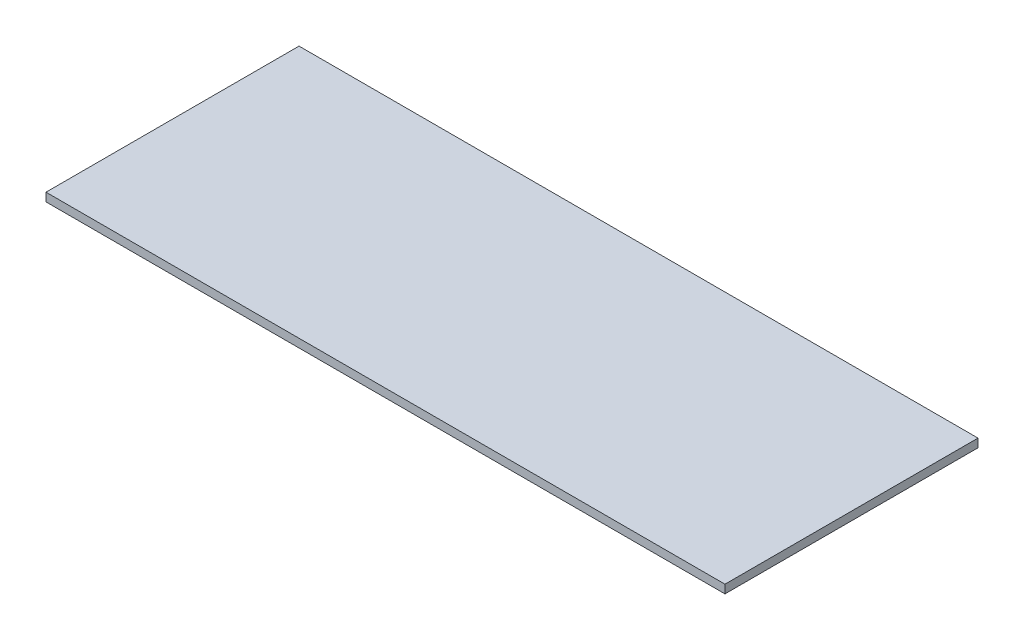
SolidWorks part; units mm, degrees
ref_plane "Front Plane" through (0, 0, 0) normal (0, 0, 1) x (1, 0, 0)
ref_plane "Top Plane" through (0, 0, 0) normal (0, 1, 0) x (1, 0, 0)
ref_plane "Right Plane" through (0, 0, 0) normal (1, 0, 0) x (0, 0, -1)
sketch "Sketch1" plane through (0, 0, 0) normal (0, 1, 0) x (1, 0, 0)
  line L0 (0, 88.9) -> (0, -88.9) construction
  line L1 (-381, 88.9) -> (381, 88.9)
  line L2 (-381, 88.9) -> (-381, -88.9)
  line L3 (-381, -88.9) -> (381, -88.9)
  line L4 (381, 88.9) -> (381, -88.9)
  line L5 (-381, 39.4607) -> (-381, 65.7679)
  line L7 (-381, 65.7679) -> (-381, 88.9)
  line L14 (-325.0712, -88.9) -> (-381, -88.9)
  line L19 (381, 65.7679) -> (381, 88.9)
  line L22 (-325.0712, 88.9) -> (-381, 88.9)
  line L29 (381, 39.4607) -> (381, 65.7679)
  line L33 (-381, 13.1536) -> (-381, 39.4607)
  line L37 (381, 13.1536) -> (381, 39.4607)
  line L41 (-381, -13.1536) -> (-381, 13.1536)
  line L45 (381, -13.1536) -> (381, 13.1536)
  line L49 (-381, -39.4607) -> (-381, -13.1536)
  line L53 (381, -39.4607) -> (381, -13.1536)
  line L57 (-381, -65.7679) -> (-381, -39.4607)
  line L61 (381, -65.7679) -> (381, -39.4607)
  line L65 (-381, -88.9) -> (-381, -65.7679)
  line L69 (381, -88.9) -> (381, -65.7679)
  line L74 (-265.9673, -88.9) -> (-325.0712, -88.9)
  line L78 (-265.9673, 88.9) -> (-325.0712, 88.9)
  line L82 (-206.8635, -88.9) -> (-265.9673, -88.9)
  line L86 (-206.8635, 88.9) -> (-265.9673, 88.9)
  line L90 (-147.7596, -88.9) -> (-206.8635, -88.9)
  line L93 (-147.7596, 88.9) -> (-147.7596, 92.075)
  line L94 (-147.7596, 88.9) -> (-206.8635, 88.9)
  line L98 (-88.6558, -88.9) -> (-147.7596, -88.9)
  line L102 (-88.6558, 88.9) -> (-147.7596, 88.9)
  line L103 (-147.7596, 88.9) -> (-147.7596, 92.075)
  line L105 (-29.5519, -88.9) -> (-29.5519, -92.075)
  line L106 (-29.5519, -88.9) -> (-88.6558, -88.9)
  line L110 (-29.5519, 88.9) -> (-88.6558, 88.9)
  line L114 (29.5519, -88.9) -> (-29.5519, -88.9)
  line L115 (-29.5519, -88.9) -> (-29.5519, -92.075)
  line L118 (29.5519, 88.9) -> (-29.5519, 88.9)
  line L122 (88.6558, -88.9) -> (29.5519, -88.9)
  line L126 (88.6558, 88.9) -> (29.5519, 88.9)
  line L130 (147.7596, -88.9) -> (88.6558, -88.9)
  line L134 (147.7596, 88.9) -> (88.6558, 88.9)
  line L138 (206.8635, -88.9) -> (147.7596, -88.9)
  line L142 (206.8635, 88.9) -> (147.7596, 88.9)
  line L146 (265.9673, -88.9) -> (206.8635, -88.9)
  line L150 (265.9673, 88.9) -> (206.8635, 88.9)
  line L186 (325.0712, -88.9) -> (265.9673, -88.9)
  line L190 (325.0712, 88.9) -> (265.9673, 88.9)
  line L194 (381, -88.9) -> (325.0712, -88.9)
  line L198 (381, 88.9) -> (325.0712, 88.9)
  point P8 (0, 88.9)
  point P9 (0, 0)
  dimension "D1" = 762
  dimension "D2" = 177.8
  dimension "D4" = 7
  dimension "D7" = 13
extrude "Boss-Extrude1" add sketch "Sketch1" along normal blind 6.35
sketch "Sketch4" [suppressed] plane through (0, 0, 0) normal (0, 1, 0) x (1, 0, 0)
  line L0 (0.0158, 88.9) -> (0.0158, -88.9) construction
  line L1 (-380.9842, 88.9) -> (381.0158, 88.9)
  line L2 (-380.9842, 88.9) -> (-380.9842, -88.9)
  line L3 (-380.9842, -88.9) -> (381.0158, -88.9)
  line L4 (381.0158, 88.9) -> (381.0158, -88.9)
  line L5 (-381, 39.4607) -> (-381, 65.7679)
  line L6 (-380.9842, 65.7679) -> (-384.1592, 65.7679)
  line L7 (-380.9842, 65.7679) -> (-380.9842, 92.075)
  line L8 (-380.9842, 92.075) -> (-384.1592, 92.075)
  line L9 (-384.1592, 65.7679) -> (-384.1592, 92.075)
  line L10 (-325.0554, -88.9) -> (-384.1592, -88.9)
  line L11 (-325.0554, -88.9) -> (-325.0554, -92.075)
  line L12 (-325.0554, -92.075) -> (-384.1592, -92.075)
  line L13 (-384.1592, -88.9) -> (-384.1592, -92.075)
  line L14 (381.0158, 65.7679) -> (384.1908, 65.7679)
  line L15 (381.0158, 65.7679) -> (381.0158, 92.075)
  line L16 (381.0158, 92.075) -> (384.1908, 92.075)
  line L17 (384.1908, 65.7679) -> (384.1908, 92.075)
  line L18 (-325.0554, 88.9) -> (-384.1592, 88.9)
  line L19 (-325.0554, 88.9) -> (-325.0554, 92.075)
  line L20 (-325.0554, 92.075) -> (-384.1592, 92.075)
  line L21 (-384.1592, 88.9) -> (-384.1592, 92.075)
  line L22 (-381, 39.4607) -> (-384.175, 39.4607)
  line L23 (-384.175, 39.4607) -> (-384.1592, 65.7679)
  line L24 (-381, 65.7679) -> (-384.1592, 65.7679)
  line L25 (381, 39.4607) -> (381, 65.7679)
  line L26 (381, 39.4607) -> (384.175, 39.4607)
  line L27 (384.175, 39.4607) -> (384.175, 65.7679)
  line L28 (381, 65.7679) -> (384.175, 65.7679)
  line L29 (-381, 13.1536) -> (-381, 39.4607)
  line L30 (-381, 13.1536) -> (-384.175, 13.1536)
  line L31 (-384.175, 13.1536) -> (-384.175, 39.4607)
  line L32 (-381, 39.4607) -> (-384.175, 39.4607)
  line L33 (381, 13.1536) -> (381, 39.4607)
  line L34 (381, 13.1536) -> (384.175, 13.1536)
  line L35 (384.175, 13.1536) -> (384.175, 39.4607)
  line L36 (381, 39.4607) -> (384.175, 39.4607)
  line L37 (-381, -13.1536) -> (-381, 13.1536)
  line L38 (-381, -13.1536) -> (-384.175, -13.1536)
  line L39 (-384.175, -13.1536) -> (-384.175, 13.1536)
  line L40 (-381, 13.1536) -> (-384.175, 13.1536)
  line L41 (381, -13.1536) -> (381, 13.1536)
  line L42 (381, -13.1536) -> (384.175, -13.1536)
  line L43 (384.175, -13.1536) -> (384.175, 13.1536)
  line L44 (381, 13.1536) -> (384.175, 13.1536)
  line L45 (-381, -39.4607) -> (-381, -13.1536)
  line L46 (-381, -39.4607) -> (-384.175, -39.4607)
  line L47 (-384.175, -39.4607) -> (-384.175, -13.1536)
  line L48 (-381, -13.1536) -> (-384.175, -13.1536)
  line L49 (381, -39.4607) -> (381, -13.1536)
  line L50 (381, -39.4607) -> (384.175, -39.4607)
  line L51 (384.175, -39.4607) -> (384.175, -13.1536)
  line L52 (381, -13.1536) -> (384.175, -13.1536)
  line L53 (-381, -65.7679) -> (-381, -39.4607)
  line L54 (-381, -65.7679) -> (-384.175, -65.7679)
  line L55 (-384.175, -65.7679) -> (-384.175, -39.4607)
  line L56 (-381, -39.4607) -> (-384.175, -39.4607)
  line L57 (381, -65.7679) -> (381, -39.4607)
  line L58 (381, -65.7679) -> (384.175, -65.7679)
  line L59 (384.175, -65.7679) -> (384.175, -39.4607)
  line L60 (381, -39.4607) -> (384.175, -39.4607)
  line L61 (-381, -92.075) -> (-381, -65.7679)
  line L62 (-381, -92.075) -> (-384.175, -92.075)
  line L63 (-384.175, -92.075) -> (-384.175, -65.7679)
  line L64 (-381, -65.7679) -> (-384.175, -65.7679)
  line L65 (381, -92.075) -> (381, -65.7679)
  line L66 (381, -92.075) -> (384.175, -92.075)
  line L67 (384.175, -92.075) -> (384.175, -65.7679)
  line L68 (381, -65.7679) -> (384.175, -65.7679)
  line L69 (-265.9673, -88.9) -> (-265.9673, -92.075)
  line L70 (-265.9673, -88.9) -> (-325.0554, -88.9)
  line L71 (-325.0554, -88.9) -> (-325.0554, -92.075)
  line L72 (-265.9673, -92.075) -> (-325.0554, -92.075)
  line L73 (-265.9673, 88.9) -> (-265.9673, 92.075)
  line L74 (-265.9673, 88.9) -> (-325.0712, 88.9)
  line L75 (-325.0712, 88.9) -> (-325.0712, 92.075)
  line L76 (-265.9673, 92.075) -> (-325.0712, 92.075)
  line L77 (-206.8635, -88.9) -> (-206.8635, -92.075)
  line L78 (-206.8635, -88.9) -> (-265.9673, -88.9)
  line L79 (-265.9673, -88.9) -> (-265.9673, -92.075)
  line L80 (-206.8635, -92.075) -> (-265.9673, -92.075)
  line L81 (-206.8635, 88.9) -> (-206.8635, 92.075)
  line L82 (-206.8635, 88.9) -> (-265.9673, 88.9)
  line L83 (-265.9673, 88.9) -> (-265.9673, 92.075)
  line L84 (-206.8635, 92.075) -> (-265.9673, 92.075)
  line L85 (-147.7596, -88.9) -> (-147.7596, -92.075)
  line L86 (-147.7596, -88.9) -> (-206.8635, -88.9)
  line L87 (-206.8635, -88.9) -> (-206.8635, -92.075)
  line L88 (-147.7596, -92.075) -> (-206.8635, -92.075)
  line L89 (-147.7596, 88.9) -> (-147.7596, 92.075)
  line L90 (-147.7596, 88.9) -> (-206.8635, 88.9)
  line L91 (-206.8635, 88.9) -> (-206.8635, 92.075)
  line L92 (-147.7596, 92.075) -> (-206.8635, 92.075)
  line L93 (-88.6558, -88.9) -> (-88.6558, -92.075)
  line L94 (-88.6558, -88.9) -> (-147.7596, -88.9)
  line L95 (-147.7596, -88.9) -> (-147.7596, -92.075)
  line L96 (-88.6558, -92.075) -> (-147.7596, -92.075)
  line L97 (-88.6558, 88.9) -> (-88.6558, 92.075)
  line L98 (-88.6558, 88.9) -> (-147.7596, 88.9)
  line L99 (-147.7596, 88.9) -> (-147.7596, 92.075)
  line L100 (-88.6558, 92.075) -> (-147.7596, 92.075)
  line L101 (-29.5519, -88.9) -> (-29.5519, -92.075)
  line L102 (-29.5519, -88.9) -> (-88.6558, -88.9)
  line L103 (-88.6558, -88.9) -> (-88.6558, -92.075)
  line L104 (-29.5519, -92.075) -> (-88.6558, -92.075)
  line L105 (-29.5519, 88.9) -> (-29.5519, 92.075)
  line L106 (-29.5519, 88.9) -> (-88.6558, 88.9)
  line L107 (-88.6558, 88.9) -> (-88.6558, 92.075)
  line L108 (-29.5519, 92.075) -> (-88.6558, 92.075)
  line L109 (29.5519, -88.9) -> (29.5519, -92.075)
  line L110 (29.5519, -88.9) -> (-29.5519, -88.9)
  line L111 (-29.5519, -88.9) -> (-29.5519, -92.075)
  line L112 (29.5519, -92.075) -> (-29.5519, -92.075)
  line L113 (29.5519, 88.9) -> (29.5519, 92.075)
  line L114 (29.5519, 88.9) -> (-29.5519, 88.9)
  line L115 (-29.5519, 88.9) -> (-29.5519, 92.075)
  line L116 (29.5519, 92.075) -> (-29.5519, 92.075)
  line L117 (88.6558, -88.9) -> (88.6558, -92.075)
  line L118 (88.6558, -88.9) -> (29.5519, -88.9)
  line L119 (29.5519, -88.9) -> (29.5519, -92.075)
  line L120 (88.6558, -92.075) -> (29.5519, -92.075)
  line L121 (88.6558, 88.9) -> (88.6558, 92.075)
  line L122 (88.6558, 88.9) -> (29.5519, 88.9)
  line L123 (29.5519, 88.9) -> (29.5519, 92.075)
  line L124 (88.6558, 92.075) -> (29.5519, 92.075)
  line L125 (147.7596, -88.9) -> (147.7596, -92.075)
  line L126 (147.7596, -88.9) -> (88.6558, -88.9)
  line L127 (88.6558, -88.9) -> (88.6558, -92.075)
  line L128 (147.7596, -92.075) -> (88.6558, -92.075)
  line L129 (147.7596, 88.9) -> (147.7596, 92.075)
  line L130 (147.7596, 88.9) -> (88.6558, 88.9)
  line L131 (88.6558, 88.9) -> (88.6558, 92.075)
  line L132 (147.7596, 92.075) -> (88.6558, 92.075)
  line L133 (206.8635, -88.9) -> (206.8635, -92.075)
  line L134 (206.8635, -88.9) -> (147.7596, -88.9)
  line L135 (147.7596, -88.9) -> (147.7596, -92.075)
  line L136 (206.8635, -92.075) -> (147.7596, -92.075)
  line L137 (206.8635, 88.9) -> (206.8635, 92.075)
  line L138 (206.8635, 88.9) -> (147.7596, 88.9)
  line L139 (147.7596, 88.9) -> (147.7596, 92.075)
  line L140 (206.8635, 92.075) -> (147.7596, 92.075)
  line L141 (265.9673, -88.9) -> (265.9673, -92.075)
  line L142 (265.9673, -88.9) -> (206.8635, -88.9)
  line L143 (206.8635, -88.9) -> (206.8635, -92.075)
  line L144 (265.9673, -92.075) -> (206.8635, -92.075)
  line L145 (265.9673, 88.9) -> (265.9673, 92.075)
  line L146 (265.9673, 88.9) -> (206.8635, 88.9)
  line L147 (206.8635, 88.9) -> (206.8635, 92.075)
  line L148 (265.9673, 92.075) -> (206.8635, 92.075)
  line L149 (325.0712, -88.9) -> (325.0712, -92.075)
  line L150 (325.0712, -88.9) -> (265.9673, -88.9)
  line L151 (265.9673, -88.9) -> (265.9673, -92.075)
  line L152 (325.0712, -92.075) -> (265.9673, -92.075)
  line L153 (325.0712, 88.9) -> (325.0712, 92.075)
  line L154 (325.0712, 88.9) -> (265.9673, 88.9)
  line L155 (265.9673, 88.9) -> (265.9673, 92.075)
  line L156 (325.0712, 92.075) -> (265.9673, 92.075)
  line L157 (384.175, -88.9) -> (384.175, -92.075)
  line L158 (384.175, -88.9) -> (325.0712, -88.9)
  line L159 (325.0712, -88.9) -> (325.0712, -92.075)
  line L160 (384.175, -92.075) -> (325.0712, -92.075)
  line L161 (384.175, 88.9) -> (384.175, 92.075)
  line L162 (384.175, 88.9) -> (325.0712, 88.9)
  line L163 (325.0712, 88.9) -> (325.0712, 92.075)
  line L164 (384.175, 92.075) -> (325.0712, 92.075)
  point P7 (0.0158, 88.9)
  dimension "D1" = 762
  dimension "D2" = 177.8
  dimension "D3" = 184.15
  dimension "D4" = 768.35
  dimension "D5" = 26.3071
  dimension "D6" = 59.1038
sketch "Sketch2" plane through (0, 6.35, 0) normal (0, 1, 0) x (1, 0, 0)
  line L0 (-123.825, 0) -> (123.825, 0) construction
  line L1 (-130.175, 15.4404) -> (-123.825, 15.4404) construction
  line L2 (-130.175, 15.4404) -> (-130.175, -15.4404) construction
  line L3 (-130.175, -15.4404) -> (-123.825, -15.4404) construction
  line L4 (-123.825, 15.4404) -> (-123.825, -15.4404) construction
  line L5 (123.825, 14.3164) -> (130.175, 14.3164) construction
  line L6 (123.825, 14.3164) -> (123.825, -14.3164) construction
  line L7 (123.825, -14.3164) -> (130.175, -14.3164) construction
  line L8 (130.175, 14.3164) -> (130.175, -14.3164) construction
  line L9 (-130.9687, 24.6215) -> (-123.0313, 24.6215) construction
  line L10 (-127, 24.6215) -> (-127, 15.4404) construction
  line L12 (-123.0312, 76.2) -> (-116.6812, 76.2)
  line L13 (-123.0312, 76.2) -> (-123.0313, 88.9)
  line L14 (-123.0313, 88.9) -> (-116.6812, 88.9)
  line L15 (-116.6812, 76.2) -> (-116.6812, 88.9)
  line L16 (-123.0313, 24.6215) -> (-123.0312, 76.2) construction
  line L18 (-116.6812, -88.9) -> (-123.0313, -88.9)
  line L19 (-116.6812, -88.9) -> (-116.6812, -76.2)
  line L20 (-116.6812, -76.2) -> (-123.0313, -76.2)
  line L21 (-123.0313, -88.9) -> (-123.0313, -76.2)
  line L31 (-381, 88.9) -> (381, 88.9) construction
  line L32 (-381, -88.9) -> (381, -88.9) construction
  line L33 (130.9688, 76.2) -> (130.9688, 88.9)
  line L34 (130.9688, 76.2) -> (137.3188, 76.2)
  line L35 (137.3188, 76.2) -> (137.3188, 88.9)
  line L36 (130.9688, 88.9) -> (137.3188, 88.9)
  line L37 (137.3188, -88.9) -> (137.3188, -76.2)
  line L38 (137.3188, -88.9) -> (130.9688, -88.9)
  line L39 (130.9688, -88.9) -> (130.9688, -76.2)
  line L40 (137.3188, -76.2) -> (130.9688, -76.2)
  line L41 (123.0313, 24.6215) -> (130.9688, 24.6215) construction
  line L42 (127, 24.6215) -> (127, 14.3164) construction
  line L43 (130.9688, 24.6215) -> (130.9688, 76.2) construction
  point P10 (0, 0)
  point P43 (127, 14.3164)
  dimension "D1" = 6.35
  dimension "D2" = 7.9375
  dimension "D4" = 6.35
  dimension "D5" = 12.7
  dimension "D3" = 254
  dimension "D6" = 2
extrude "Cut-Extrude1" [suppressed] cut sketch "Sketch2" against normal through all
sketch "Sketch5" plane through (0, 6.35, 0) normal (0, 1, 0) x (1, 0, 0)
  line L0 (-381, 88.9) -> (-381, -88.9) construction
  line L1 (-387.35, 95.25) -> (387.35, 95.25)
  line L2 (-387.35, 95.25) -> (-387.35, -95.25)
  line L3 (-387.35, -95.25) -> (387.35, -95.25)
  line L4 (387.35, 95.25) -> (387.35, -95.25)
  line L5 (-381, -88.9) -> (381, -88.9) construction
  line L7 (-381, 88.9) -> (381, 88.9)
  line L8 (-381, 88.9) -> (-381, -88.9)
  line L9 (-381, -88.9) -> (381, -88.9)
  line L10 (381, 88.9) -> (381, -88.9)
  dimension "D1" = 774.7
  dimension "D2" = 190.5
  dimension "D3" = 6.35
  dimension "0.25" = 6.35
extrude "Boss-Extrude2" add sketch "Sketch5" against normal up to surface (6.35 mm away) up to face at (0, 0, 0)
sketch "Sketch7" plane through (0, 0, 0) normal (0, -1, 0) x (1, 0, 0)
  line L7 (387.35, 95.25) -> (-387.35, 95.25) construction
  line L8 (123.82, 95.25) -> (387.35, 95.25)
  line L9 (123.82, 95.25) -> (123.82, -95.25)
  line L10 (123.82, -95.25) -> (387.35, -95.25)
  line L11 (387.35, 95.25) -> (387.35, -95.25)
  line L12 (-387.35, 95.25) -> (-387.35, -95.25) construction
  dimension "D1" = 511.17
extrude "Cut-Extrude2" cut sketch "Sketch7" against normal through all
equation "\"Height\"= 12in"
equation "\"Depth\"= 7in"
equation "\"WallThickness\"= 0.25in"
equation "\"FloorThickness\"= 0.25in"
equation "\"D1@Sketch1\"=\"Width\""
equation "\"D2@Sketch1\"=\"Depth\""
equation "\"D1@Boss-Extrude1\"=\"FloorThickness\""
equation "\"D1@Sketch2\"=\"WallThickness\""
equation "\"D2@Sketch2\"=\"WallThickness\"+(1/16in)"
equation "\"D4@Sketch2\"=\"WallThickness\""
equation "\"Width\" = 30in"
